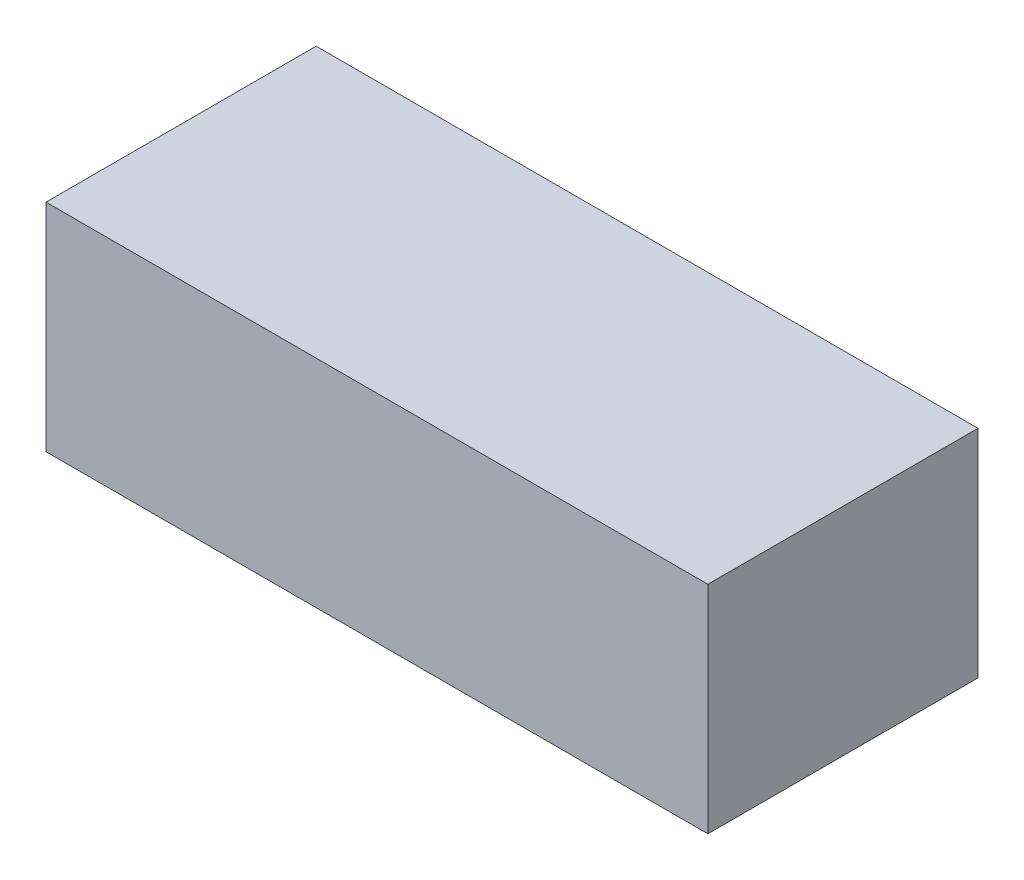
SolidWorks part; units mm, degrees
ref_plane "Front Plane" through (0, 0, 0) normal (0, 0, 1) x (1, 0, 0)
ref_plane "Top Plane" through (0, 0, 0) normal (0, 1, 0) x (1, 0, 0)
ref_plane "Right Plane" through (0, 0, 0) normal (1, 0, 0) x (0, 0, -1)
sketch "Sketch1" plane through (0, 0, 0) normal (0, 0, 1) x (1, 0, 0)
  line L1 (-7.615, 16.1266) -> (4.635, 16.1266)
  line L2 (-7.615, 16.1266) -> (-7.615, 12.1266)
  line L3 (-7.615, 12.1266) -> (4.635, 12.1266)
  line L4 (4.635, 16.1266) -> (4.635, 12.1266)
  dimension "D1" = 12.25
  dimension "D2" = 4
extrude "Boss-Extrude1" add sketch "Sketch1" along normal blind 5
